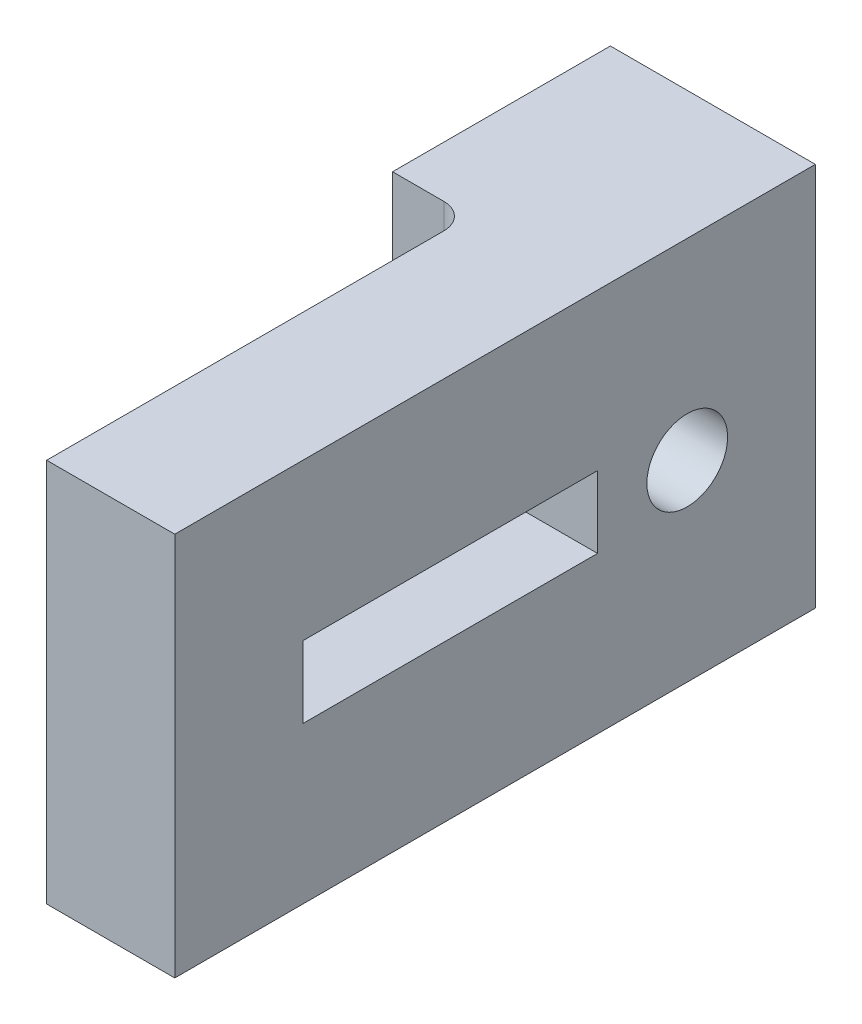
SolidWorks part; units mm, degrees
ref_plane "前视基准面" through (0, 0, 0) normal (0, 0, 1) x (1, 0, 0)
ref_plane "上视基准面" through (0, 0, 0) normal (0, 1, 0) x (1, 0, 0)
ref_plane "右视基准面" through (0, 0, 0) normal (1, 0, 0) x (0, 0, -1)
other "Configuration Table"
sketch "草图1" plane through (0, 0, 0) normal (0, 1, 0) x (1, 0, 0)
  line L0 (-5.7479, 13.0588) -> (2.2521, 13.0588)
  line L1 (2.2521, 13.0588) -> (2.2521, -11.9412)
  line L2 (2.2521, -11.9412) -> (-2.7479, -11.9412)
  line L3 (-2.7479, -11.9412) -> (-2.7479, 4.5588)
  line L4 (-2.7479, 4.5588) -> (-5.7479, 4.5588)
  line L5 (-5.7479, 4.5588) -> (-5.7479, 13.0588)
  dimension "D1" = 8
  dimension "D2" = 8.5
  dimension "D3" = 25
  dimension "D4" = 5
extrude "凸台-拉伸1" add sketch "草图1" along normal blind 15
ref_plane "基准面1" through (-5.7479, 0, 0) normal (-1, 0, 0) x (0, 0, 1)
sketch "草图2" plane through (-5.7479, 0, 0) normal (-1, 0, 0) x (0, 0, 1)
  line L0 (-13.0588, 15) -> (-13.0588, 0) construction
  line L1 (-4.5588, 15) -> (-4.5588, 0) construction
  line L3 (-13.0588, 7.5) -> (-4.5588, 7.5)
  circle A0 centre (-8.0588, 7.5) radius 1.575
  dimension "D2" = 3.15
  dimension "D1" = 5
extrude "切除-拉伸1" cut sketch "草图2" against normal blind 15 contours L3 A0 | L3 A0
ref_plane "基准面2" through (-2.7479, 0, 0) normal (-1, 0, 0) x (0, 0, 1)
sketch "草图3" plane through (-2.7479, 0, 0) normal (-1, 0, 0) x (0, 0, 1)
  line L0 (-4.5588, 7.5) -> (11.9412, 7.5)
  line L1 (-4.5588, 15) -> (-4.5588, 0) construction
  line L2 (11.9412, 15) -> (11.9412, 0) construction
  line L3 (-4.5588, 8.9) -> (6.9412, 8.9)
  line L4 (6.9412, 8.9) -> (6.9412, 6.1)
  line L5 (6.9412, 6.1) -> (-4.5588, 6.1)
  line L6 (-4.5588, 6.1) -> (-4.5588, 8.9)
  point P8 (6.9412, 7.5)
  dimension "D1" = 2.8
  dimension "D2" = 5
fillet "圆角1" radius 1 1 edges at (-2.7479, 7.5, -4.5588)
extrude "切除-拉伸2" cut sketch "草图3" against normal blind 10 contours L6 L0 L4 L3 | L6 L5 L4 L0
